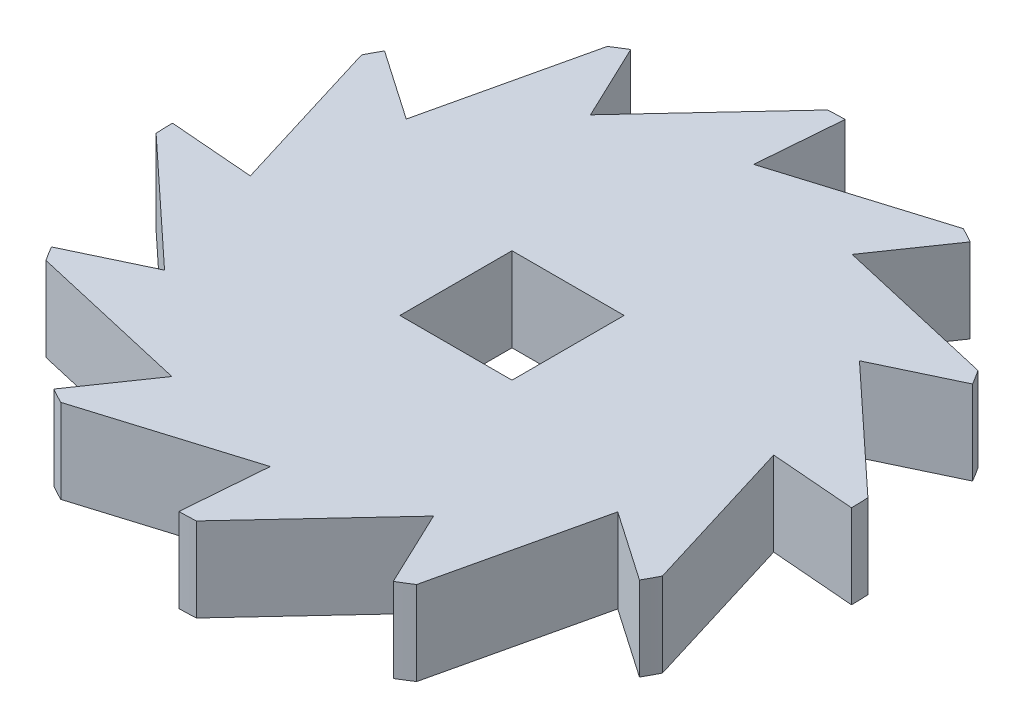
SolidWorks part; units mm, degrees
ref_plane "Piano frontale" through (0, 0, 0) normal (0, 0, 1) x (1, 0, 0)
ref_plane "Piano superiore" through (0, 0, 0) normal (0, 1, 0) x (1, 0, 0)
ref_plane "Piano destro" through (0, 0, 0) normal (1, 0, 0) x (0, 0, -1)
sketch "Schizzo1" plane through (0, 0, 0) normal (0, 1, 0) x (1, 0, 0)
  line L1 (-5, -5) -> (5, -5)
  line L2 (-5, -5) -> (-5, 5)
  line L3 (-5, 5) -> (5, 5)
  line L4 (5, -5) -> (5, 5)
  line L5 (-5, -5) -> (5, 5) construction
  line L6 (-5, 5) -> (5, -5) construction
  circle A0 centre (0, 0) radius 30
  point P0 (0, 0)
  point P6 (0, 5)
  dimension "D2" = 60
  dimension "D1" = 10
extrude "Estrusione-Estrusione1" add sketch "Schizzo1" along normal blind 7.5
sketch "Schizzo2" plane through (0, 7.5, 0) normal (0, 1, 0) x (1, 0, 0)
  line L0 (10.4542, 19.8873) -> (25.0338, 16.532)
  line L1 (14.7522, 26.1222) -> (10.4542, 19.8873)
  line L2 (-0.2853, 29.9986) -> (-0.89, 22.45)
  line L3 (-0.89, 22.45) -> (13.4139, 26.8341)
  line L4 (-5, 5) -> (-5, -5) construction
  line L5 (18.9973, 11.9958) -> (29.9459, 1.8002)
  line L6 (25.8369, 15.2464) -> (18.9973, 11.9958)
  line L7 (22.45, 0.89) -> (26.8341, -13.4139)
  line L8 (29.9986, 0.2853) -> (22.45, 0.89)
  line L9 (19.8873, -10.4542) -> (16.532, -25.0338)
  line L10 (26.1222, -14.7522) -> (19.8873, -10.4542)
  line L11 (11.9958, -18.9973) -> (1.8002, -29.9459)
  line L12 (15.2464, -25.8369) -> (11.9958, -18.9973)
  line L13 (0.89, -22.45) -> (-13.4139, -26.8341)
  line L14 (0.2853, -29.9986) -> (0.89, -22.45)
  line L15 (-10.4542, -19.8873) -> (-25.0338, -16.532)
  line L16 (-14.7522, -26.1222) -> (-10.4542, -19.8873)
  line L17 (-18.9973, -11.9958) -> (-29.9459, -1.8002)
  line L18 (-25.8369, -15.2464) -> (-18.9973, -11.9958)
  line L19 (-22.45, -0.89) -> (-26.8341, 13.4139)
  line L20 (-29.9986, -0.2853) -> (-22.45, -0.89)
  line L21 (-19.8873, 10.4542) -> (-16.532, 25.0338)
  line L22 (-26.1222, 14.7522) -> (-19.8873, 10.4542)
  line L23 (-11.9958, 18.9973) -> (-1.8002, 29.9459)
  line L24 (-15.2464, 25.8369) -> (-11.9958, 18.9973)
  circle A1 centre (0, 0) radius 30 construction
  circle A2 centre (0, 0) radius 30
  circle A3 centre (0, 0) radius 30
  point P3 (0, 0)
  point P47 (0, 0)
  circle M4 centre (0, 0) radius 30
  dimension "D2" = 68.38
  dimension "D3" = 17.45
  dimension "D4" = 4.11
  dimension "D5" = 4.58
  dimension "D7" = 1.5149
  dimension "D1" = 0
  dimension "D6" = 12
extrude "Taglio-Estrusione1" cut sketch "Schizzo2" against normal through all both and the other way through all contours L22 L21 M4 | L20 L19 M4 | L18 L17 M4 | L16 L15 M4 | L14 L13 M4 | L12 L11 M4 | L10 L9 M4 | L8 L7 M4 | L6 L5 M4 | L1 L0 M4 | L2 L3 M4 | L24 L23 M4
